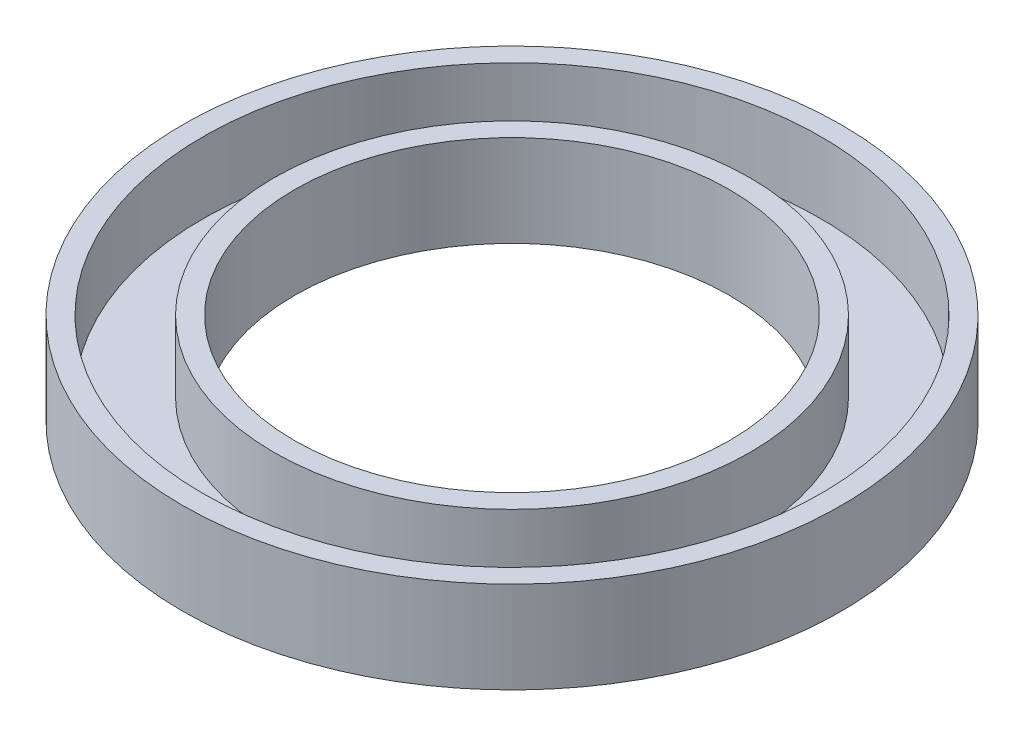
SolidWorks part; units mm, degrees
ref_plane "前视基准面" through (0, 0, 0) normal (0, 0, 1) x (1, 0, 0)
ref_plane "上视基准面" through (0, 0, 0) normal (0, 1, 0) x (1, 0, 0)
ref_plane "右视基准面" through (0, 0, 0) normal (1, 0, 0) x (0, 0, -1)
other "Configuration Table"
sketch "草图1" plane through (0, 0, 0) normal (0, 0, 1) x (1, 0, 0)
  line L0 (0, 32.5418) -> (0, -28.913) construction
  line L1 (17.4, 1.9577) -> (17.4, -3.2423)
  line L2 (17.4, -3.2423) -> (22.6, -3.2423)
  line L3 (22.6, -3.2423) -> (22.6, 1.9577)
  line L4 (15.9, 1.9577) -> (15.9, -4.7423)
  line L5 (15.9, -4.7423) -> (24.1, -4.7423)
  line L6 (24.1, -4.7423) -> (24.1, 1.9577)
  line L7 (15.9, 1.9577) -> (17.4, 1.9577)
  line L8 (22.6, 1.9577) -> (24.1, 1.9577)
  dimension "D1" = 34.8
  dimension "D2" = 45.2
  dimension "D3" = 5.2
  dimension "D4" = 5.2
  dimension "D5" = 1.5
revolve "旋转1" add sketch "草图1" angle 360 about L0
